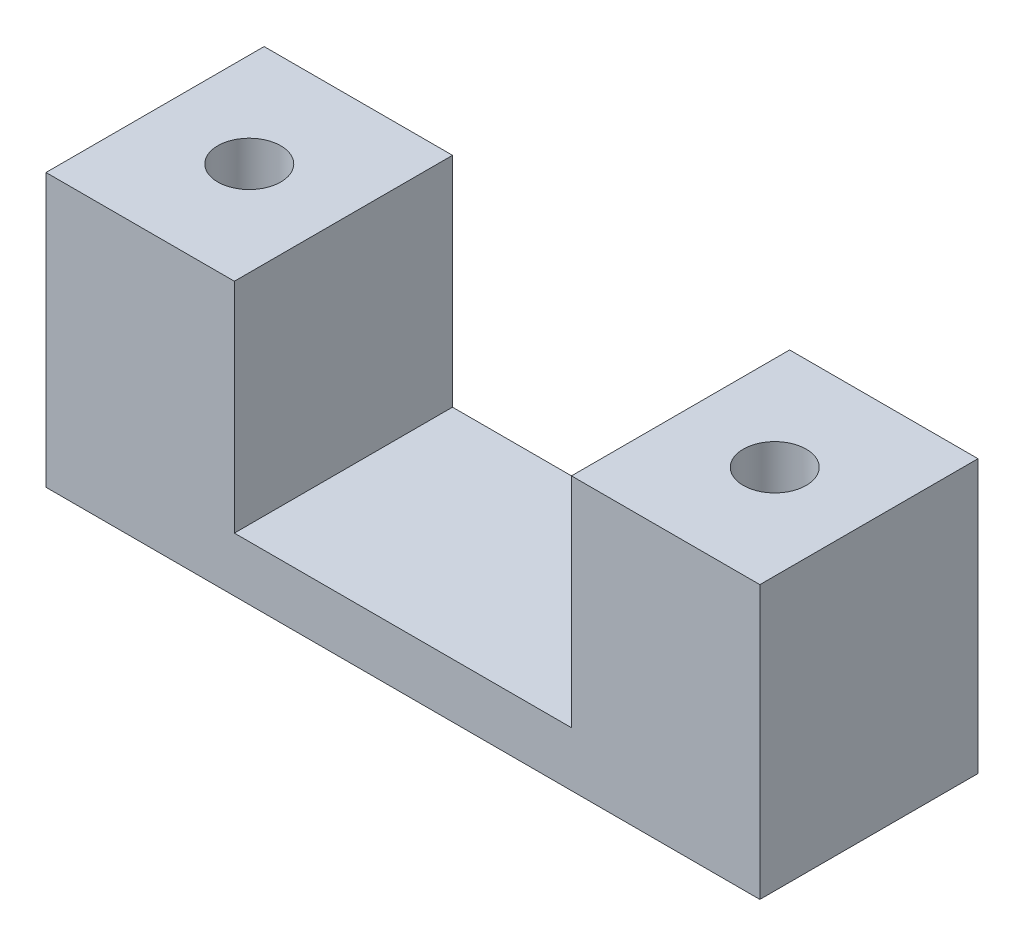
SolidWorks part; units mm, degrees
ref_plane "Front Plane" through (0, 0, 0) normal (0, 0, 1) x (1, 0, 0)
ref_plane "Top Plane" through (0, 0, 0) normal (0, 1, 0) x (1, 0, 0)
ref_plane "Right Plane" through (0, 0, 0) normal (1, 0, 0) x (0, 0, -1)
sketch "Sketch1" plane through (0, 0, 0) normal (0, 1, 0) x (1, 0, 0)
  line L1 (0, 0) -> (72, 0)
  line L2 (0, 0) -> (0, 22)
  line L3 (0, 22) -> (72, 22)
  line L4 (72, 0) -> (72, 22)
  line L7 (30.2143, -18.8036) -> (29.5714, -18.8036)
  dimension "D1" = 72
  dimension "D2" = 22
extrude "Boss-Extrude1" add sketch "Sketch1" along normal blind 27.5 contours L1 L4 L3 L2
sketch "Sketch2" plane through (0, 27.5, 0) normal (0, 1, 0) x (1, 0, 0)
  line L0 (0, 0) -> (72, 0) construction
  line L1 (19, 22) -> (53, 22)
  line L2 (19, 22) -> (19, 0)
  line L3 (19, 0) -> (53, 0)
  line L4 (53, 22) -> (53, 0)
  line L5 (19, 22) -> (53, 0) construction
  line L6 (19, 0) -> (53, 22) construction
  line L7 (36, 0) -> (36, 11) construction
  point P0 (36, 11)
  dimension "D1" = 34
  dimension "D2" = 22
extrude "Cut-Extrude1" cut sketch "Sketch2" against normal blind 22
sketch "Sketch3" plane through (0, 27.5, 0) normal (0, 1, 0) x (1, 0, 0)
  line L0 (36, 22) -> (36, 0) construction
  line L1 (53, 22) -> (19, 22) construction
  line L2 (19, 0) -> (53, 0) construction
  line L3 (19, 22) -> (19, 0) construction
  circle A0 centre (9.5, 11) radius 3.175
  circle A1 centre (62.5, 11) radius 3.175
  dimension "D1" = 6.35
  dimension "D2" = 9.5
extrude "Cut-Extrude2" cut sketch "Sketch3" against normal blind 69
sketch "Sketch5" plane through (0, 0, 0) normal (0, -1, 0) x (1, 0, 0)
  line L0 (36, 0) -> (36, -22) construction
  line L1 (0, 0) -> (72, 0) construction
  line L2 (0, -22) -> (72, -22) construction
  circle A0 centre (9.5, -11) radius 5.5
  circle A1 centre (62.5, -11) radius 5.5
  dimension "D1" = 11
extrude "Cut-Extrude3" cut sketch "Sketch5" against normal blind 5.5
